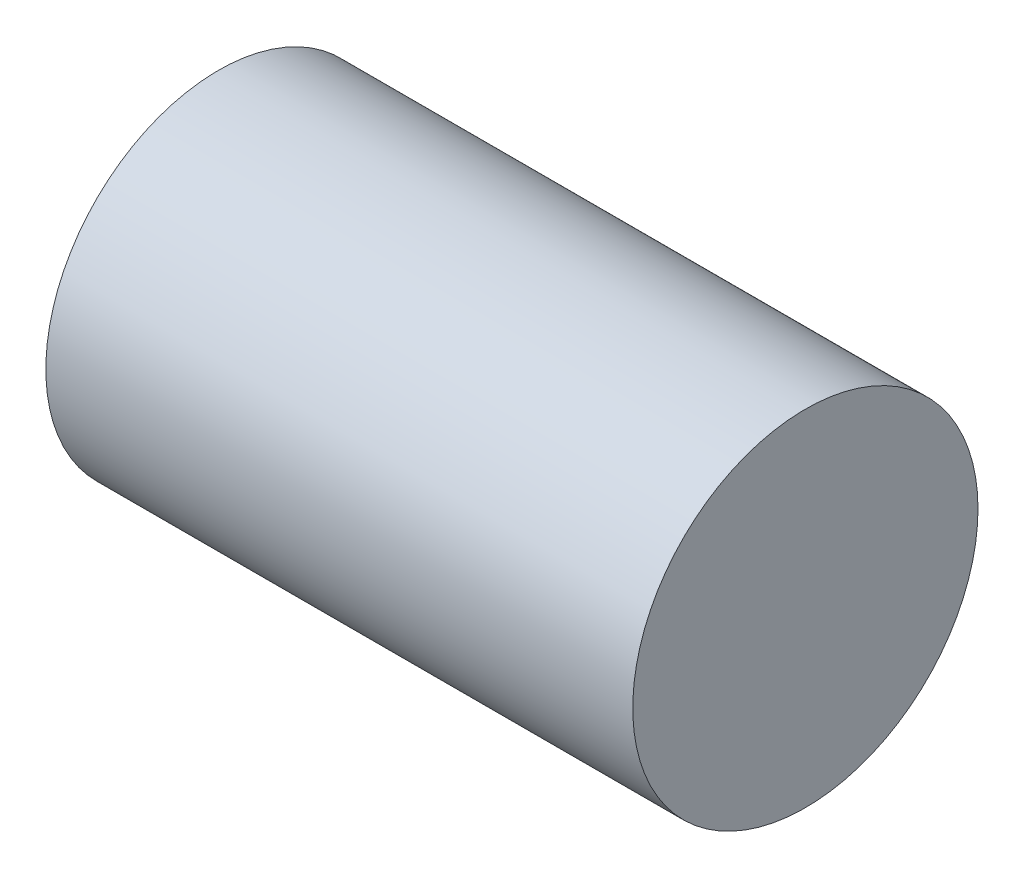
SolidWorks part; units mm, degrees
ref_plane "前视基准面" through (0, 0, 0) normal (0, 0, 1) x (1, 0, 0)
ref_plane "上视基准面" through (0, 0, 0) normal (0, 1, 0) x (1, 0, 0)
ref_plane "右视基准面" through (0, 0, 0) normal (1, 0, 0) x (0, 0, -1)
sketch "草图1" plane through (0, 0, 0) normal (1, 0, 0) x (0, 0, -1)
  circle A0 centre (0, 0) radius 2.5
  dimension "D1" = 5
extrude "凸台-拉伸1" add sketch "草图1" along normal blind 8.5
